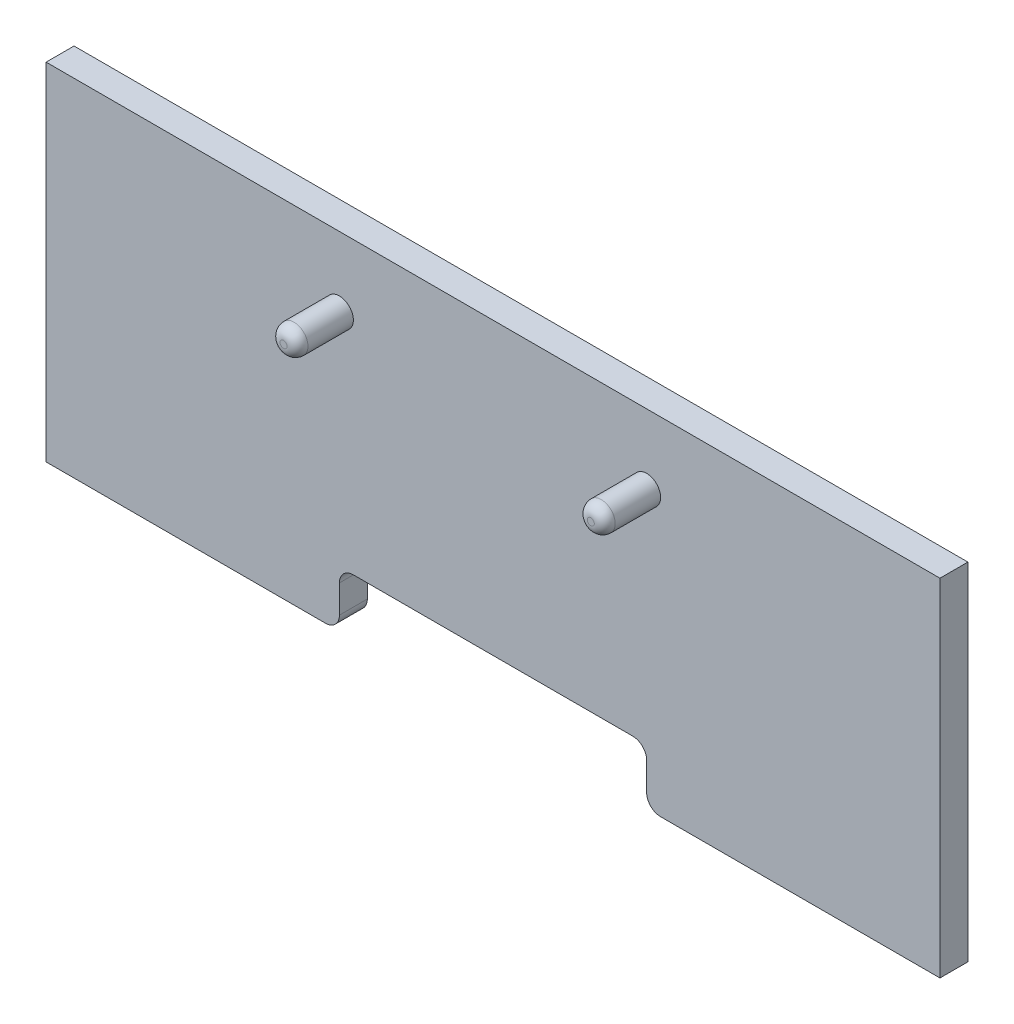
SolidWorks part; units mm, degrees
material "Copper"
ref_plane "Front Plane" through (0, 0, 0) normal (0, 0, 1) x (1, 0, 0)
ref_plane "Top Plane" through (0, 0, 0) normal (0, 1, 0) x (1, 0, 0)
ref_plane "Right Plane" through (0, 0, 0) normal (1, 0, 0) x (0, 0, -1)
sketch "Sketch1" plane through (0, 0, 0) normal (0, 0, 1) x (1, 0, 0)
  line L1 (0, 0) -> (203.2, 0)
  line L2 (0, 0) -> (0, 78.7146)
  line L3 (0, 78.7146) -> (203.2, 78.7146)
  line L4 (203.2, 0) -> (203.2, 78.7146)
  dimension "D1" = 203.2
  dimension "D2" = 78.7146
extrude "Boss-Extrude1" add sketch "Sketch1" along normal blind 6.35
sketch "Sketch2" plane through (0, 0, 6.35) normal (0, 0, 1) x (1, 0, 0)
  line L0 (0, 0) -> (203.2, 0) construction
  line L1 (66.675, 0) -> (136.525, 0)
  line L2 (66.675, 0) -> (66.675, 12.7)
  line L3 (66.675, 12.7) -> (136.525, 12.7)
  line L4 (136.525, 0) -> (136.525, 12.7)
  line L5 (101.6, 78.7146) -> (101.6, 12.7) construction
  line L6 (203.2, 78.7146) -> (0, 78.7146) construction
  dimension "D1" = 69.85
  dimension "D2" = 12.7
extrude "Cut-Extrude1" cut sketch "Sketch2" against normal through all
fillet "Fillet1" radius 3.175 4 edges at (136.525, 0, 3.175) (136.525, 12.7, 3.175) (66.675, 12.7, 3.175) (66.675, 0, 3.175)
sketch "Sketch3" plane through (0, 0, 6.35) normal (0, 0, 1) x (1, 0, 0)
  line L0 (66.675, 62.8396) -> (136.525, 62.8396) construction
  line L1 (101.6, 62.8396) -> (101.6, 78.7146) construction
  line L2 (203.2, 78.7146) -> (0, 78.7146) construction
  circle A0 centre (66.675, 62.8396) radius 3.175
  circle A1 centre (136.525, 62.8396) radius 3.175
  dimension "D1" = 6.35
  dimension "D2" = 69.85
  dimension "D3" = 15.875
extrude "Boss-Extrude2" add sketch "Sketch3" along normal blind 12.7
fillet "Fillet2" radius 2.3813 2 edges at (139.7, 62.8396, 19.05) (69.85, 62.8396, 19.05)
